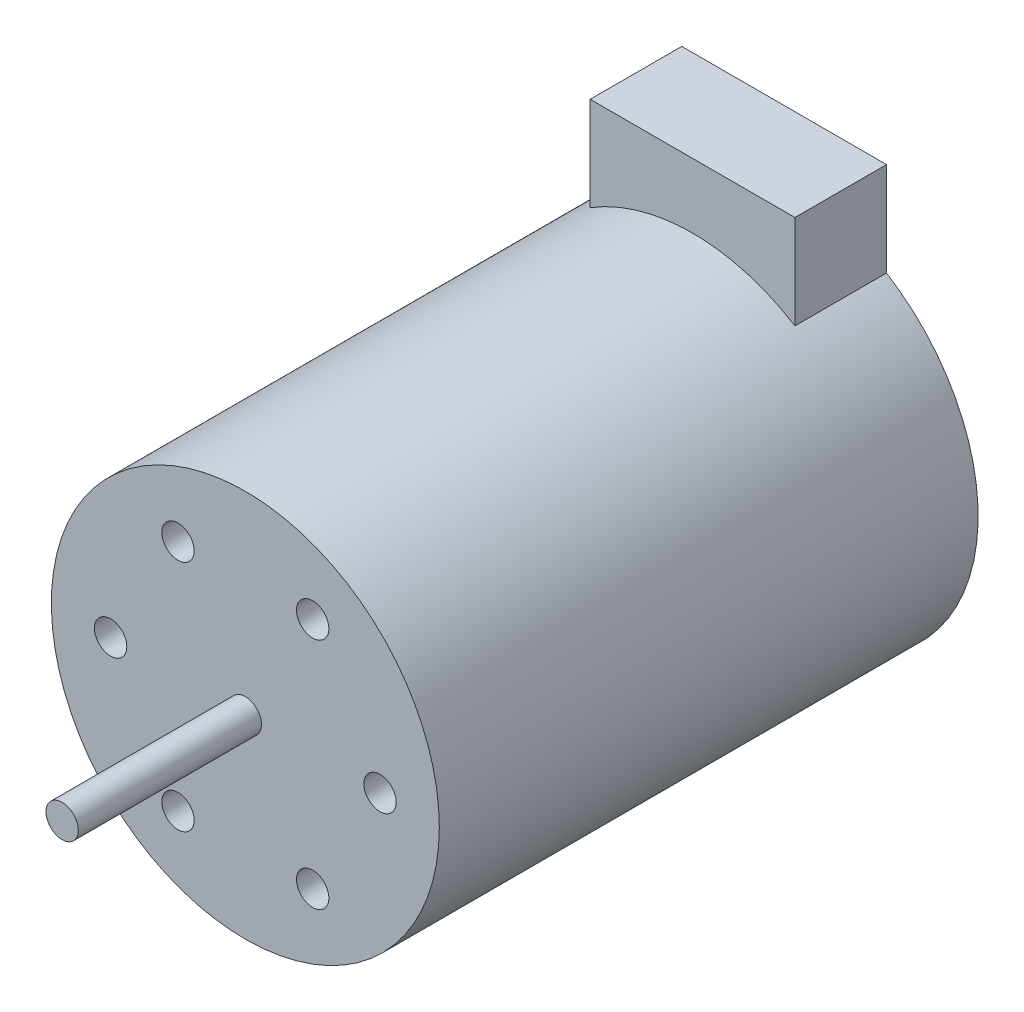
SolidWorks part; units mm, degrees
ref_plane "Front Plane" through (0, 0, 0) normal (0, 0, 1) x (1, 0, 0)
ref_plane "Top Plane" through (0, 0, 0) normal (0, 1, 0) x (1, 0, 0)
ref_plane "Right Plane" through (0, 0, 0) normal (1, 0, 0) x (0, 0, -1)
sketch "Sketch1" plane through (0, 0, 0) normal (0, 0, 1) x (1, 0, 0)
  circle A0 centre (0, 0) radius 18
  dimension "D1" = 36
extrude "Boss-Extrude1" add sketch "Sketch1" along normal blind 50
sketch "Sketch2" plane through (0, 0, 50) normal (0, 0, 1) x (1, 0, 0)
  circle A0 centre (0, 0) radius 1.5
  dimension "D1" = 3
extrude "Boss-Extrude2" add sketch "Sketch2" along normal blind 17
sketch "Sketch3" plane through (0, 0, 0) normal (0, 1, 0) x (1, 0, 0)
  line L0 (18, 0) -> (-18, 0) construction
  line L1 (-9.5, -8.5) -> (9.5, -8.5)
  line L2 (-9.5, -8.5) -> (-9.5, 0)
  line L3 (-9.5, 0) -> (9.5, 0)
  line L4 (9.5, -8.5) -> (9.5, 0)
  line L5 (-9.5, -8.5) -> (9.5, 0) construction
  line L6 (-9.5, 0) -> (9.5, -8.5) construction
  point P0 (0, -4.25)
  dimension "D1" = 8.5
  dimension "D2" = 19
  dimension "D3" = 4.25
extrude "Boss-Extrude3" add sketch "Sketch3" along normal blind 24
sketch "Sketch4" plane through (0, 0, 50) normal (0, 0, 1) x (1, 0, 0)
  circle A0 centre (12.5, 0) radius 1.5
  circle A1 centre (6.25, -10.8253) radius 1.5
  circle A2 centre (-6.25, -10.8253) radius 1.5
  circle A3 centre (-12.5, 0) radius 1.5
  circle A4 centre (-6.25, 10.8253) radius 1.5
  circle A5 centre (6.25, 10.8253) radius 1.5
  point P16 (0, 0)
  dimension "D1" = 12.5
  dimension "D3" = 3
  dimension "D2" = 6
extrude "Cut-Extrude1" cut sketch "Sketch4" against normal blind 5
